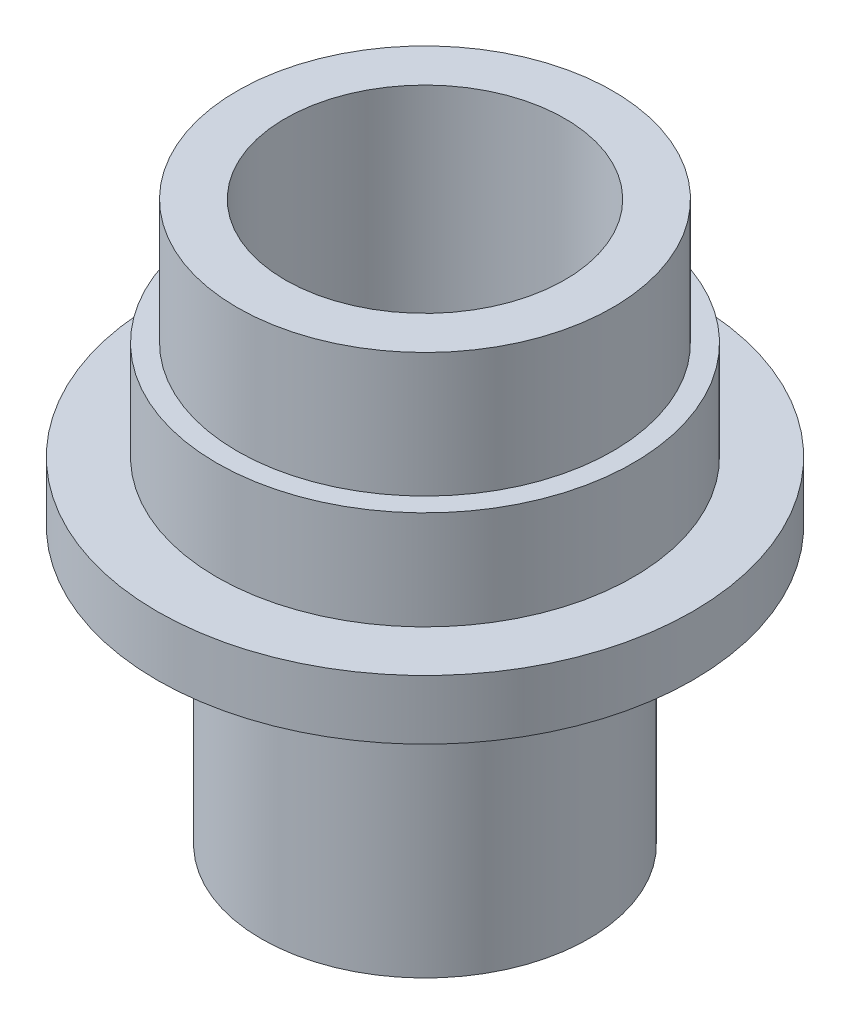
SolidWorks part; units mm, degrees
ref_plane "Alzado" through (0, 0, 0) normal (0, 0, 1) x (1, 0, 0)
ref_plane "Planta" through (0, 0, 0) normal (0, 1, 0) x (1, 0, 0)
ref_plane "Vista lateral" through (0, 0, 0) normal (1, 0, 0) x (0, 0, -1)
sketch "Croquis1" plane through (0, 0, 0) normal (0, 0, 1) x (1, 0, 0)
  line L0 (0, 0) -> (-4.7, 0)
  line L1 (-4.7, 0) -> (-4.7, 9)
  line L2 (-4.7, 9) -> (-6.31, 9)
  line L3 (-6.31, 9) -> (-6.31, 4.82)
  line L4 (-6.31, 4.82) -> (-7, 4.82)
  line L5 (-7, 4.82) -> (-7, 1.5)
  line L6 (-7, 1.5) -> (-9, 1.5)
  line L7 (-9, 1.5) -> (-9, -0.5)
  line L10 (-5.5, -9.78) -> (0, -9.78)
  line L11 (0, -9.78) -> (0, 0)
  line L12 (0, 46.5849) -> (0, -39.7468) construction
  line L13 (-9, -0.5) -> (-7, -0.5)
  line L14 (-7, -0.5) -> (-7, -1)
  line L15 (-7, -1) -> (-5.5, -1)
  line L16 (-5.5, -1) -> (-5.5, -9.78)
  point P15 (-7, 3.16)
  point P18 (-6.25, -1)
  point P19 (-5.5, -1)
  point P20 (-5.5, -9.78)
  dimension "D1" = 9
  dimension "D2" = 4.7
  dimension "D3" = 1.61
  dimension "D4" = 4.18
  dimension "D5" = 3.32
  dimension "D6" = 2
  dimension "D7" = 5.5
  dimension "D8" = 9
  dimension "D9" = 7
  dimension "D10" = 7
  dimension "D11" = 0.5
  dimension "D12" = 9.28
revolve "Revolución1" add sketch "Croquis1" angle 360 about L12
